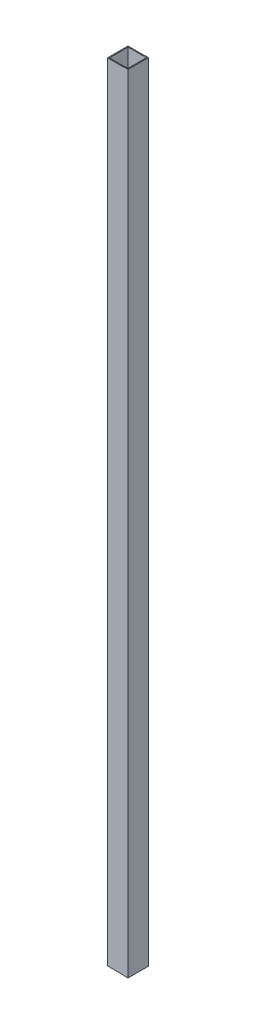
SolidWorks part; units mm, degrees
ref_plane "Front Plane" through (0, 0, 0) normal (0, 0, 1) x (1, 0, 0)
ref_plane "Top Plane" through (0, 0, 0) normal (0, 1, 0) x (1, 0, 0)
ref_plane "Right Plane" through (0, 0, 0) normal (1, 0, 0) x (0, 0, -1)
sketch "Sketch1" plane through (0, 0, 0) normal (0, 1, 0) x (1, 0, 0)
  line L0 (0, 0) -> (0, 50)
  line L1 (0, 50) -> (50, 50)
  line L2 (50, 50) -> (50, 0)
  line L3 (50, 0) -> (0, 0)
  line L4 (2.2, 47.8) -> (47.8, 47.8)
  line L5 (47.8, 47.8) -> (47.8, 2.2)
  line L6 (47.8, 2.2) -> (2.2, 2.2)
  line L7 (2.2, 2.2) -> (2.2, 47.8)
  dimension "D1" = 50
  dimension "D2" = 50
  dimension "D3" = 2.2
extrude "Boss-Extrude1" add sketch "Sketch1" along normal blind 1923
sketch "Sketch2" plane through (0, 0, 0) normal (0, 0, 1) x (1, 0, 0)
  line L0 (0, 0) -> (0, 0.5)
  line L1 (0, 1923) -> (0, 0) construction
  line L2 (0, 0.5) -> (40, 0.5)
  line L3 (40, 0.5) -> (40, 0)
  line L5 (40, 0) -> (0, 0)
  line L6 (0, 1923) -> (40, 1923)
  line L7 (0, 1923) -> (50, 1923) construction
  line L8 (40, 1923) -> (40, 1922.5)
  line L9 (40, 1922.5) -> (0, 1922.5)
  line L10 (0, 1922.5) -> (0, 1923)
  dimension "D1" = 0.5
  dimension "D2" = 40
  dimension "D3" = 0.5
  dimension "D4" = 40
extrude "Cut-Extrude2" cut sketch "Sketch2" against normal blind 50
equation "\"SquareTube_length\"=1923.0"
equation "\"D1@Boss-Extrude1\"=\"SquareTube_length\""
equation "\"SquareTube_inFront1_cutDepth50_R\"=0.5"
equation "\"D1@Sketch2\" = \"SquareTube_inFront2_cutDepth50_R\""
equation "\"SquareTube_inFront1_cutDepth50_L\"=0.5"
equation "\"D3@Sketch2\" = \"SquareTube_inFront2_cutDepth50_L\""
equation "\"CarBeamWidth\"=700.0"
equation "\"MetalSheet_3mm_length\"=5030.0"
equation "\"MetalSheet_3mm_width\"=1923.0"
equation "\"MetalSheet_3mm_FloorCut_L_length\"=1764.0"
equation "\"MetalSheet_3mm_FloorCut_L_disdance\"=1665.0"
equation "\"MetalSheet_3mm_FloorCut_R_length\"=1764.0"
equation "\"MetalSheet_3mm_FloorCut_R_disdance\"=1665.0"
equation "\"indoorHeight\"=1940.0"
equation "\"x\"=66.0"
equation "\"da\"=62.0"
equation "\"SquareTube_wheel_length\"= 750"
equation "\"channelSteel_length\"=5030.0"
equation "\"SquareTube_inFront2_cutDepth50_R\"=0.5"
equation "\"SquareTube_inFront2_cutDepth50_L\"=0.5"
equation "\"SquareTube_inFront3_cutDepth50_R\"=0.5"
equation "\"SquareTube_inFront3_cutDepth50_L\"=0.5"
equation "\"SquareTube_inFront4_cutDepth50_R\"=0.5"
equation "\"SquareTube_inFront4_cutDepth50_L\"=0.5"
equation "\"SquareTube_inFront5_cutDepth50_R\"=50"
equation "\"SquareTube_inFront5_cutDepth50_L\"=50"
equation "\"SquareTube_inFront6_cutDepth50_R\"=50"
equation "\"SquareTube_inFront6_cutDepth50_L\"=50"
equation "\"SquareTube_inFront7_cutDepth50_R\"=50"
equation "\"SquareTube_inFront7_cutDepth50_L\"=50"
equation "\"SquareTube_inFront8_cutDepth50_R\"=50"
equation "\"SquareTube_inFront8_cutDepth50_L\"=50"
equation "\"SquareTube_inFront9_cutDepth50_R\"=50"
equation "\"SquareTube_inFront9_cutDepth50_L\"=50"
equation "\"SquareTube_inFront10_cutDepth50_R\"=50"
equation "\"SquareTube_inFront10_cutDepth50_L\"=50"
equation "\"SquareTube_inBack1_cutDepth50_R\"=50"
equation "\"SquareTube_inBack1_cutDepth50_L\"=50"
equation "\"SquareTube_inBack2_cutDepth50_R\"=50"
equation "\"SquareTube_inBack2_cutDepth50_L\"=50"
equation "\"SquareTube_inBack3_cutDepth50_R\"=50"
equation "\"SquareTube_inBack3_cutDepth50_L\"=50"
equation "\"SquareTube_inBack4_cutDepth50_R\"=50"
equation "\"SquareTube_inBack4_cutDepth50_L\"=50"
equation "\"SquareTube_inBack5_cutDepth50_R\"=50"
equation "\"SquareTube_inBack5_cutDepth50_L\"=50"
equation "\"SquareTube_inBack6_cutDepth50_R\"=0.5"
equation "\"SquareTube_inBack6_cutDepth50_L\"=0.5"
equation "\"SquareTube_inFront11_cutDepth50_R\"=50"
equation "\"SquareTube_inFront11_cutDepth50_L\"=50"
equation "\"SquareTube_inFront12_cutDepth50_R\"=50"
equation "\"SquareTube_inFront12_cutDepth50_L\"=50"
equation "\"SquareTube_inFront13_cutDepth50_R\"=50"
equation "\"SquareTube_inFront13_cutDepth50_L\"=50"
equation "\"SquareTube_inFront14_cutDepth50_R\"=50"
equation "\"SquareTube_inFront14_cutDepth50_L\"=50"
equation "\"SquareTube_inBack7_cutDepth50_R\"=0.5"
equation "\"SquareTube_inBack7_cutDepth50_L\"=0.5"
equation "\"SquareTube_inBack8_cutDepth50_R\"=0.5"
equation "\"SquareTube_inBack8_cutDepth50_L\"=0.5"
